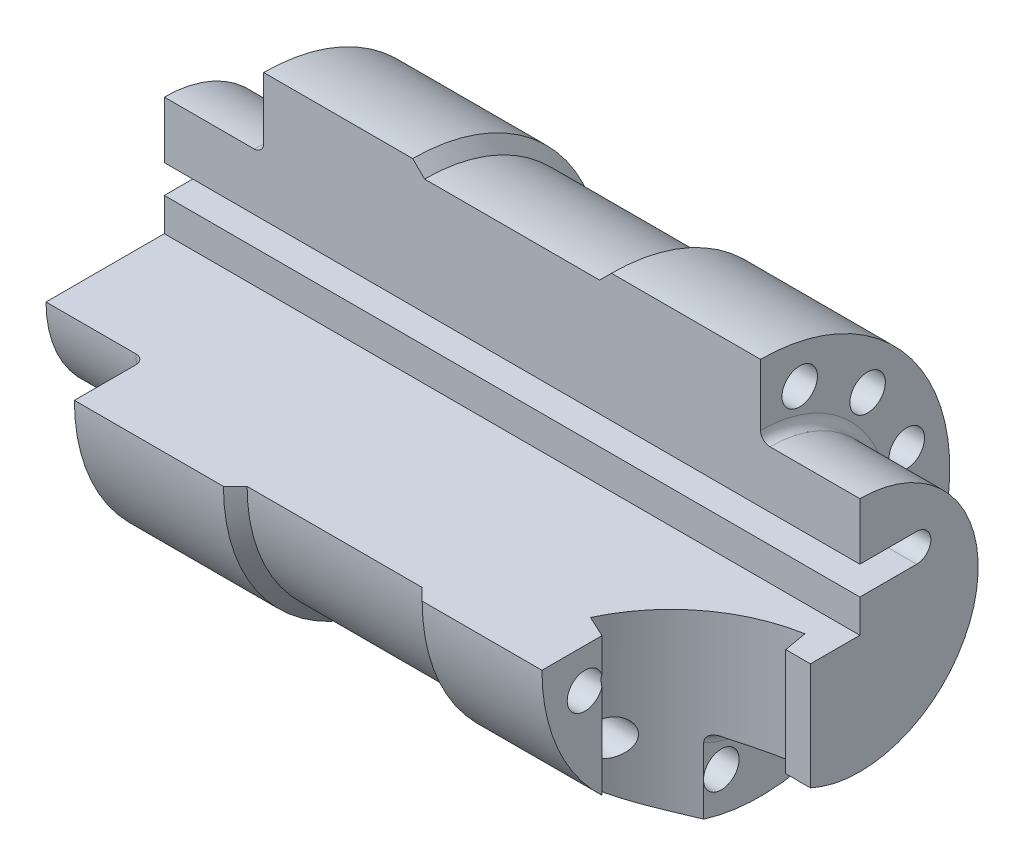
SolidWorks part; units mm, degrees
material "AISI 1020"
ref_plane "Plan de face" through (0, 0, 0) normal (0, 0, 1) x (1, 0, 0)
ref_plane "Plan de dessus" through (0, 0, 0) normal (0, 1, 0) x (1, 0, 0)
ref_plane "Plan de droite" through (0, 0, 0) normal (1, 0, 0) x (0, 0, -1)
sketch "Esquisse1" plane through (0, 0, 0) normal (0, 0, 1) x (1, 0, 0)
  line L0 (0, 0) -> (29.5663, 0)
  line L1 (29.5663, 0) -> (29.5663, 25)
  line L2 (29.5663, 25) -> (10.5663, 25)
  line L3 (8.5663, 27) -> (8.5663, 40)
  line L4 (8.5663, 40) -> (-22.9337, 40)
  line L5 (-22.9337, 40) -> (-25.4337, 37.5)
  line L6 (-25.4337, 37.5) -> (-62.4337, 37.5)
  line L7 (-62.4337, 37.5) -> (-64.9337, 40)
  line L8 (-64.9337, 40) -> (-96.4337, 40)
  line L9 (-96.4337, 40) -> (-96.4337, 27)
  line L10 (-98.4337, 25) -> (-117.4337, 25)
  line L11 (-117.4337, 25) -> (-117.4337, 0)
  line L12 (-117.4337, 0) -> (0, 0)
  line L13 (-130.7689, 0) -> (47.3428, 0) construction
  arc A0 (-98.4337, 25) -> (-96.4337, 27) centre (-98.4337, 27) ccw
  arc A1 (10.5663, 25) -> (8.5663, 27) centre (10.5663, 27) cw
  dimension "D11" = 2
  dimension "D13" = 2
  dimension "D1" = 25
  dimension "D2" = 40
  dimension "D3" = 21
  dimension "D4" = 21
  dimension "D5" = 31.5
  dimension "D6" = 31.5
  dimension "D7" = 2.5
  dimension "D8" = 2.5
  dimension "D9" = 225
  dimension "D10" = 225
  dimension "D12" = 25
  dimension "D14" = 147
revolve "Révolution1" add sketch "Esquisse1" angle 360 about L13
sketch "Esquisse2" plane through (-117.4337, 0, 0) normal (-1, 0, 0) x (0, 0, 1)
  line L0 (0, 0) -> (0, 7)
  line L1 (0, 0) -> (43.4498, 0)
  line L2 (0, 0) -> (0, 7)
  line L3 (0, 44.4974) -> (43.4498, 44.4974)
  line L4 (43.4498, 0) -> (43.4498, 44.4974)
  line L9 (0, 10) -> (-12, 10)
  line L10 (0, 10) -> (-12, 10) construction
  line L11 (0, 7) -> (-12, 7)
  line L12 (0, 13) -> (-12, 13)
  line L13 (0, 13) -> (0, 44.4974)
  arc A0 (0, 7) -> (0, 13) centre (0, 10) ccw
  arc A1 (-12, 13) -> (-12, 7) centre (-12, 10) ccw
  point P7 (-6, 10)
  dimension "D2" = 3
  dimension "D1" = 12
  dimension "D3" = 7
extrude "Enlèv. mat.-Extru.1" cut sketch "Esquisse2" against normal through all
sketch "Esquisse3" plane through (-117.4337, 0, 0) normal (-1, 0, 0) x (0, 0, 1)
  line L0 (0, 0) -> (0, 48.007) construction
  line L1 (0, 0) -> (-13.9068, 51.901)
  circle A2 centre (-8.2822, 30.9096) radius 3.75
  circle A3 centre (8.2822, 30.9096) radius 3.75
  circle A4 centre (22.6274, 22.6274) radius 3.75
  circle A5 centre (30.9096, 8.2822) radius 3.75
  circle A6 centre (30.9096, -8.2822) radius 3.75
  circle A7 centre (22.6274, -22.6274) radius 3.75
  circle A8 centre (8.2822, -30.9096) radius 3.75
  circle A9 centre (-8.2822, -30.9096) radius 3.75
  circle A10 centre (-22.6274, -22.6274) radius 3.75
  circle A11 centre (-30.9096, -8.2822) radius 3.75
  circle A12 centre (-30.9096, 8.2822) radius 3.75
  circle A13 centre (-22.6274, 22.6274) radius 3.75
  dimension "D2" = 12
  dimension "D1" = 15
extrude "Enlèv. mat.-Extru.2" cut sketch "Esquisse3" against normal through all contours L1 A2 | L1 A2 | A13 | A12 | A11 | A10 | A9 | A8 | A7 | A6
sketch "Esquisse4" plane through (0, 0, 0) normal (0, 1, 0) x (1, 0, 0)
  line L0 (8.5663, -40) -> (55.0268, -40) construction
  line L1 (29.5663, -25) -> (29.5663, -47.2098) construction
  line L2 (29.5663, -40) -> (23.1808, -3.7859)
  line L3 (29.5663, -40) -> (-10.728, -21.2105)
  line L4 (29.5663, 0) -> (29.5663, -25) construction
  line L5 (8.5663, -40) -> (-22.9337, -40) construction
  line L6 (24.3568, -10.4558) -> (29.5663, -10.4558)
  line L7 (24.3568, -10.4558) -> (23.4886, -5.5317)
  line L8 (2.377, -27.3215) -> (2.377, -40)
  arc A1 (24.3568, -10.4558) -> (2.377, -27.3215) centre (29.5663, -40) ccw
  arc A2 (23.4886, -5.5317) -> (-2.1545, -25.2084) centre (29.5663, -40) ccw
  line M10 (-22.9337, -40) -> (8.5663, -40)
  line M11 (8.5663, -40) -> (8.5663, -27)
  arc M12 (8.5663, -27) -> (10.5663, -25) centre (10.5663, -27) cw
  line M13 (10.5663, -25) -> (29.5663, -25)
  line M14 (29.5663, -25) -> (29.5663, 0)
  dimension "D1" = 10
  dimension "D3" = 35
  dimension "D4" = 30
  dimension "D2" = 25
extrude "Enlèv. mat.-Extru.3" cut sketch "Esquisse4" against normal through all contours L3 L8 M10 M11 | L2 A1 L3 M11 M12 M13 | L2 A2 L3 A1 | L6 L2 M13 M14
equation "\"A\"= 147"
equation "\"B\"= 21"
equation "\"C\"= 31.5"
equation "\"D3@Esquisse1\"=\"B\""
equation "\"D4@Esquisse1\"=\"B\""
equation "\"D5@Esquisse1\"=\"C\""
equation "\"D6@Esquisse1\"=\"C\""
equation "\"D14@Esquisse1\"=\"A\""
